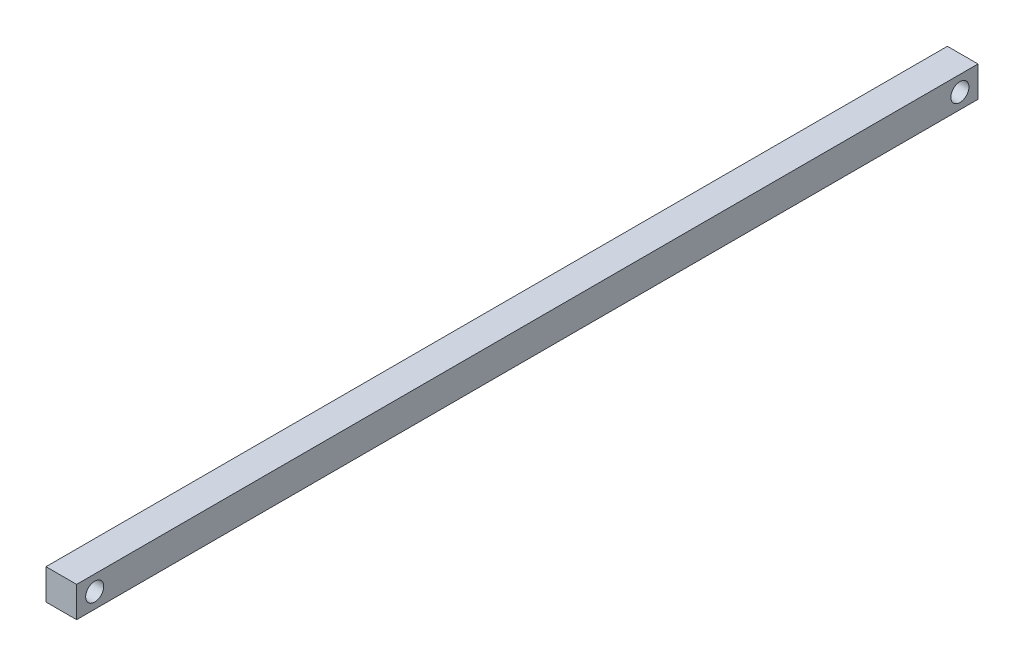
SolidWorks part; units mm, degrees
ref_plane "Front Plane" through (0, 0, 0) normal (0, 0, 1) x (1, 0, 0)
ref_plane "Top Plane" through (0, 0, 0) normal (0, 1, 0) x (1, 0, 0)
ref_plane "Right Plane" through (0, 0, 0) normal (1, 0, 0) x (0, 0, -1)
sketch "Sketch1" plane through (0, 0, 0) normal (1, 0, 0) x (0, 0, -1)
  line L1 (0, 0) -> (373.8, 0)
  line L2 (0, 0) -> (0, 12.7)
  line L3 (0, 12.7) -> (373.8, 12.7)
  line L4 (373.8, 0) -> (373.8, 12.7)
  circle A0 centre (7.5, 6.35) radius 3.75
  circle A1 centre (366.3, 6.35) radius 3.75
  point P9 (0, 0)
  point P10 (0, 0)
  point P11 (0, 6.35)
  dimension "D2" = 358.8
  dimension "D5" = 7.5
  dimension "D1" = 12.7
  dimension "D3" = 7.5
  dimension "D4" = 7.5
extrude "Boss-Extrude1" add sketch "Sketch1" along normal blind 12.7
